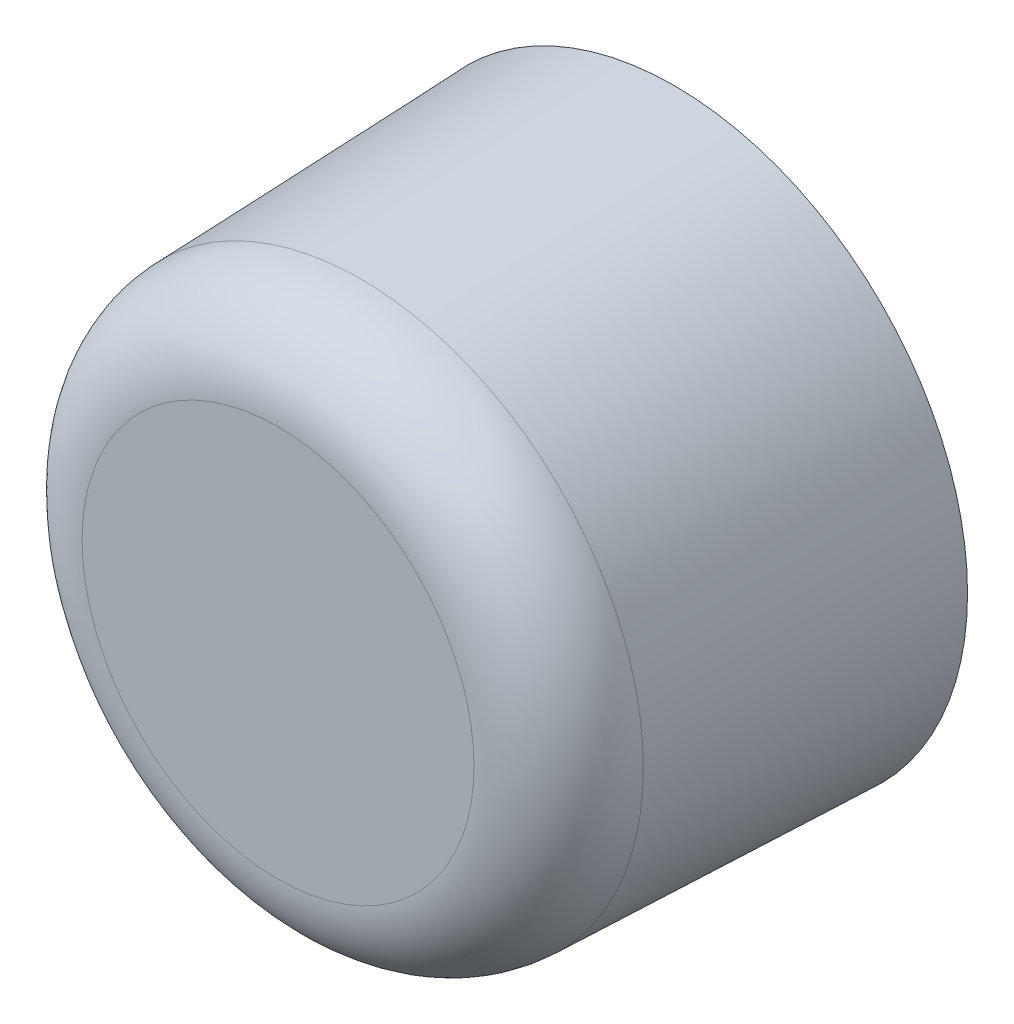
SolidWorks part; units mm, degrees
ref_plane "前视基准面" through (0, 0, 0) normal (0, 0, 1) x (1, 0, 0)
ref_plane "上视基准面" through (0, 0, 0) normal (0, 1, 0) x (1, 0, 0)
ref_plane "右视基准面" through (0, 0, 0) normal (1, 0, 0) x (0, 0, -1)
sketch "草图1" plane through (0, 0, 0) normal (0, 0, 1) x (1, 0, 0)
  circle A0 centre (0, 0) radius 3.4
  dimension "D1" = 6.8
extrude "凸台-拉伸1" add sketch "草图1" along normal blind 4.6 draft 2
fillet "圆角1" radius 1 1 edges at (3.2394, 0, 4.6)
